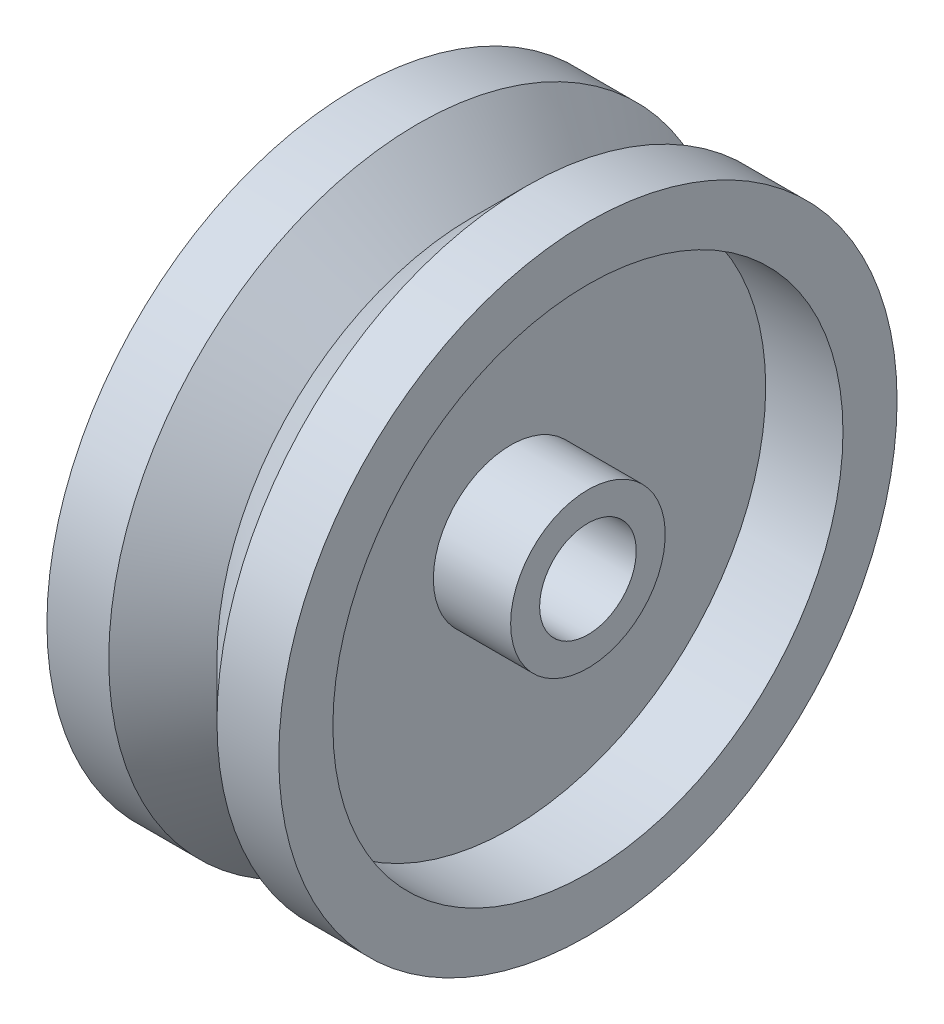
SolidWorks part; units mm, degrees
ref_plane "Front Plane" through (0, 0, 0) normal (0, 0, 1) x (1, 0, 0)
ref_plane "Top Plane" through (0, 0, 0) normal (0, 1, 0) x (1, 0, 0)
ref_plane "Right Plane" through (0, 0, 0) normal (1, 0, 0) x (0, 0, -1)
sketch "Sketch1" plane through (0, 0, 0) normal (0, 0, 1) x (1, 0, 0)
  line L0 (0, 0) -> (7.5, 0) construction
  line L1 (0, 16.5) -> (3.5, 20)
  line L2 (3.5, 20) -> (7.5, 20)
  line L3 (7.5, 20) -> (7.5, 16.5)
  line L4 (7.5, 16.5) -> (2.5, 16.5)
  line L5 (2.5, 16.5) -> (2.5, 5)
  line L6 (2.5, 5) -> (7.5, 5)
  line L7 (7.5, 5) -> (7.5, 3.125)
  line L8 (7.5, 3.125) -> (-7.5, 3.125)
  line L9 (0, 16.5) -> (0, 22.1248) construction
  line L10 (-7.5, 5) -> (-7.5, 3.125)
  line L11 (-2.5, 5) -> (-7.5, 5)
  line L12 (-2.5, 16.5) -> (-2.5, 5)
  line L13 (-7.5, 16.5) -> (-2.5, 16.5)
  line L14 (-7.5, 20) -> (-7.5, 16.5)
  line L15 (0, 16.5) -> (-3.5, 20)
  line L16 (-3.5, 20) -> (-7.5, 20)
  point P6 (3.3183, 20)
  point P12 (0, 22.1248)
  point P16 (0, 3.125)
  dimension "D1" = 7.5
  dimension "D2" = 2.5
  dimension "D3" = 3.125
  dimension "D4" = 5
  dimension "D5" = 45
  dimension "D6" = 20
  dimension "D7" = 16.5
revolve "Revolve1" add sketch "Sketch1" angle 360 about L0
